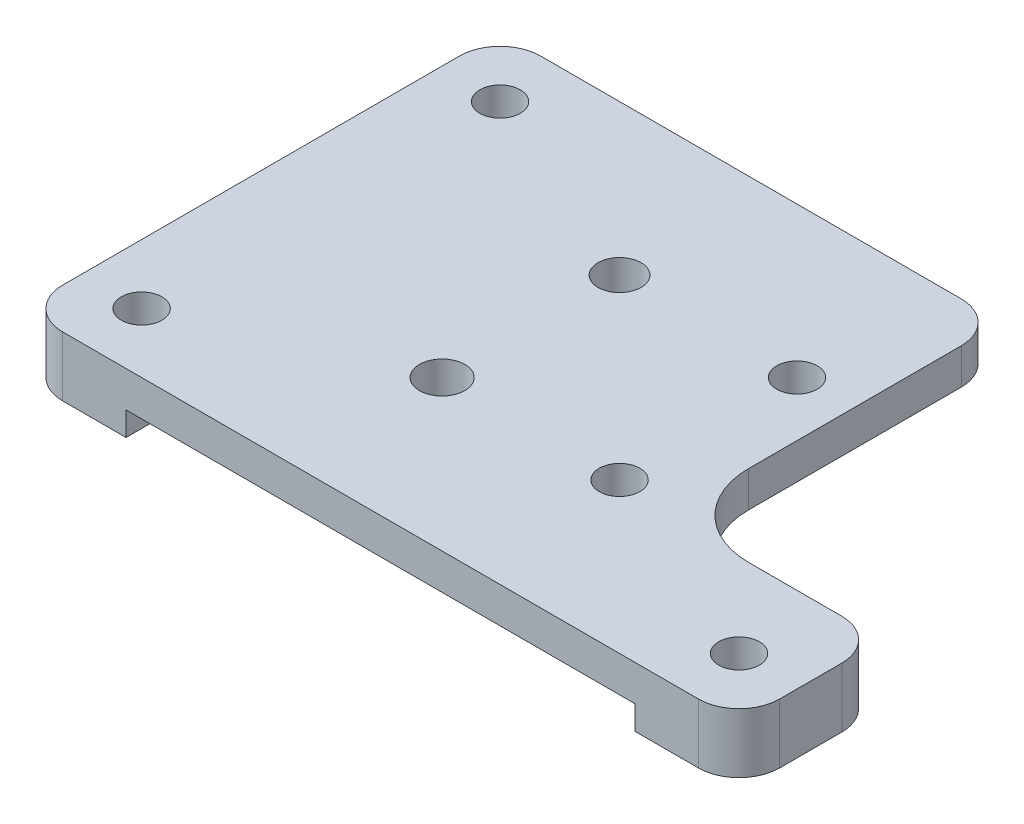
SolidWorks part; units mm, degrees
ref_plane "前视基准面" through (0, 0, 0) normal (0, 0, 1) x (1, 0, 0)
ref_plane "上视基准面" through (0, 0, 0) normal (0, 1, 0) x (1, 0, 0)
ref_plane "右视基准面" through (0, 0, 0) normal (1, 0, 0) x (0, 0, -1)
other "Configuration Table"
sketch "草图2" plane through (0, 0, 0) normal (0, 1, 0) x (1, 0, 0)
  line L0 (0, 0) -> (0, 7.425) construction
  line L1 (-25, 15) -> (25, 15)
  line L2 (-25, 15) -> (-25, -15)
  line L3 (-25, -15) -> (25, -15)
  line L4 (25, 15) -> (25, -15)
  line L5 (-25, 15) -> (25, -15) construction
  line L6 (-25, -15) -> (25, 15) construction
  line L7 (-12, -20) -> (12, -20)
  line L8 (-12, -20) -> (-12, 20)
  line L9 (-12, 20) -> (12, 20)
  line L10 (12, -20) -> (12, 20)
  line L11 (-12, -20) -> (12, 20) construction
  line L12 (-12, 20) -> (12, -20) construction
  line L13 (0, 7.425) -> (-7.425, 7.425) construction
  line L14 (-7.425, 7.425) -> (-7.425, -7.425) construction
  line L15 (-7.425, -7.425) -> (7.425, -7.425) construction
  line L16 (7.425, -7.425) -> (7.425, 7.425) construction
  line L18 (-12, 20) -> (-30, 20)
  line L19 (-12, 20) -> (-12, -20)
  line L20 (-12, -20) -> (-30, -20)
  line L21 (-30, 20) -> (-30, -20)
  line L22 (12, -20) -> (30, -20)
  line L23 (12, -20) -> (12, -8)
  line L24 (12, -8) -> (30, -8)
  line L25 (30, -20) -> (30, -8)
  circle A0 centre (-25, 15) radius 1.7
  circle A1 centre (-25, -15) radius 1.7
  circle A2 centre (25, -15) radius 1.7
  circle A3 centre (7.425, 7.425) radius 1.7
  circle A4 centre (7.425, -7.425) radius 1.7
  circle A5 centre (-7.425, -7.425) radius 1.7
  circle A6 centre (-7.425, 7.425) radius 1.7
  point P0 (0, 0)
  point P9 (0, 0)
  dimension "D3" = 3.4
  dimension "D4" = 3.4
  dimension "D5" = 3.4
  dimension "D12" = 3.4
  dimension "D13" = 3.4
  dimension "D14" = 3.4
  dimension "D15" = 3.4
  dimension "D1" = 30
  dimension "D2" = 50
  dimension "D6" = 40
  dimension "D7" = 24
  dimension "D8" = 7.425
  dimension "D9" = 7.425
  dimension "D10" = 14.85
  dimension "D11" = 14.85
  dimension "D16" = 40
  dimension "D17" = 18
  dimension "D18" = 12
  dimension "D19" = 18
extrude "凸台-拉伸1" add sketch "草图2" along normal blind 3 contours A2 L4 L24 L10 L3 | A2 L3 L10 L22 L25 L24 L4 | L7 L10 L3 L8 | L3 L10 L1 L8 A6 A5 A4 A3 | L1 L10 L9 L8 | A1 L3 L8 L1 A0 L2 | A1 L2 A0 L1 L8 L18 L21 L20 L3
fillet "圆角2" radius 6.8 1 edges at (12, 1.5, 8)
sketch "草图4" plane through (0, 0, 0) normal (0, -1, 0) x (1, 0, 0)
  line L1 (-30, 20) -> (-21.3, 20)
  line L2 (-30, 20) -> (-30, -20)
  line L3 (-30, -20) -> (-21.3, -20)
  line L4 (-21.3, 20) -> (-21.3, -20)
  line L5 (-30, -20) -> (12, -20) construction
  line L7 (30, 20) -> (21.3, 20)
  line L8 (30, 20) -> (30, 8)
  line L9 (30, 8) -> (21.3, 8)
  line L10 (21.3, 20) -> (21.3, 8)
  line L11 (18.8, 8) -> (30, 8) construction
  line L12 (23.3, 15) -> (26.7, 15) construction
  line L13 (26.7, 15) -> (25, 15) construction
  line L14 (-26.7, 15) -> (-23.3, 15) construction
  line L15 (-26.7, -15) -> (-23.3, -15) construction
  circle A0 centre (25, 15) radius 1.7 construction
  circle A1 centre (25, 15) radius 1.7
  circle A2 centre (-25, 15) radius 1.7 construction
  circle A3 centre (-25, 15) radius 1.7
  circle A4 centre (-25, -15) radius 1.7 construction
  circle A5 centre (-25, -15) radius 1.7
  dimension "D1" = 40
  dimension "D2" = 8.7
  dimension "D3" = 12
  dimension "D4" = 8.7
extrude "凸台-拉伸2" add sketch "草图4" along normal blind 2 contours L2 L1 L4 L3 | L8 L7 L10 L9 | A3 | A1 | A5
fillet "圆角3" radius 3.4 5 edges at (12, 1.5, -20) (-30, 0.5, -20) (-30, 0.5, 20) (30, 0.5, 8) (30, 0.5, 20)
sketch "草图5" plane through (0, 3, 0) normal (0, 1, 0) x (1, 0, 0)
  circle A1 centre (-7.425, -7.425) radius 1.9
  circle A3 centre (-7.425, 7.425) radius 1.8
  dimension "D1" = 3.6
  dimension "D2" = 3.8
extrude "切除-拉伸1" cut sketch "草图5" against normal blind 10
